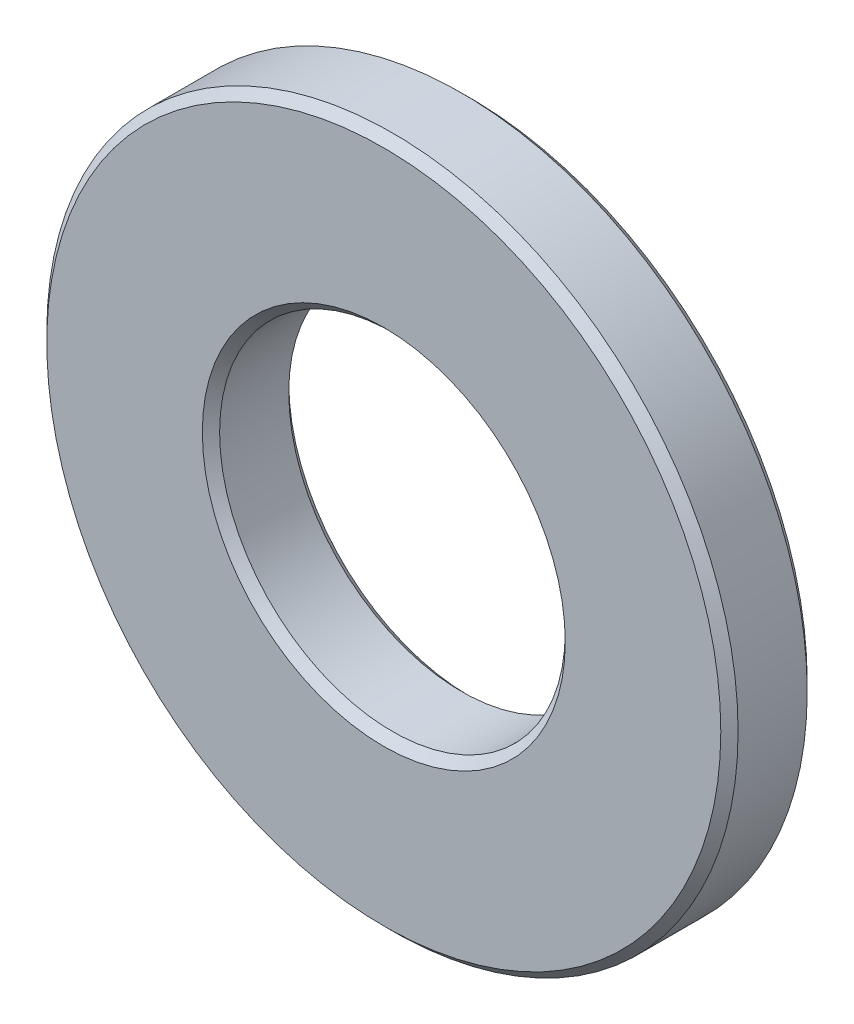
SolidWorks part; units mm, degrees
ref_plane "前视基准面" through (0, 0, 0) normal (0, 0, 1) x (1, 0, 0)
ref_plane "上视基准面" through (0, 0, 0) normal (0, 1, 0) x (1, 0, 0)
ref_plane "右视基准面" through (0, 0, 0) normal (1, 0, 0) x (0, 0, -1)
sketch "草图1" plane through (0, 0, 0) normal (0, 0, 1) x (1, 0, 0)
  circle A0 centre (0, 0) radius 2
  circle A1 centre (0, 0) radius 4
  dimension "D1" = 4
  dimension "D2" = 8
extrude "凸台-拉伸1" add sketch "草图1" along normal mid plane 1
chamfer "倒角1" distance 0.1 angle 45 4 edges at (2, 0, 0.5) (2, 0, -0.5) (4, 0, -0.5) (4, 0, 0.5)
